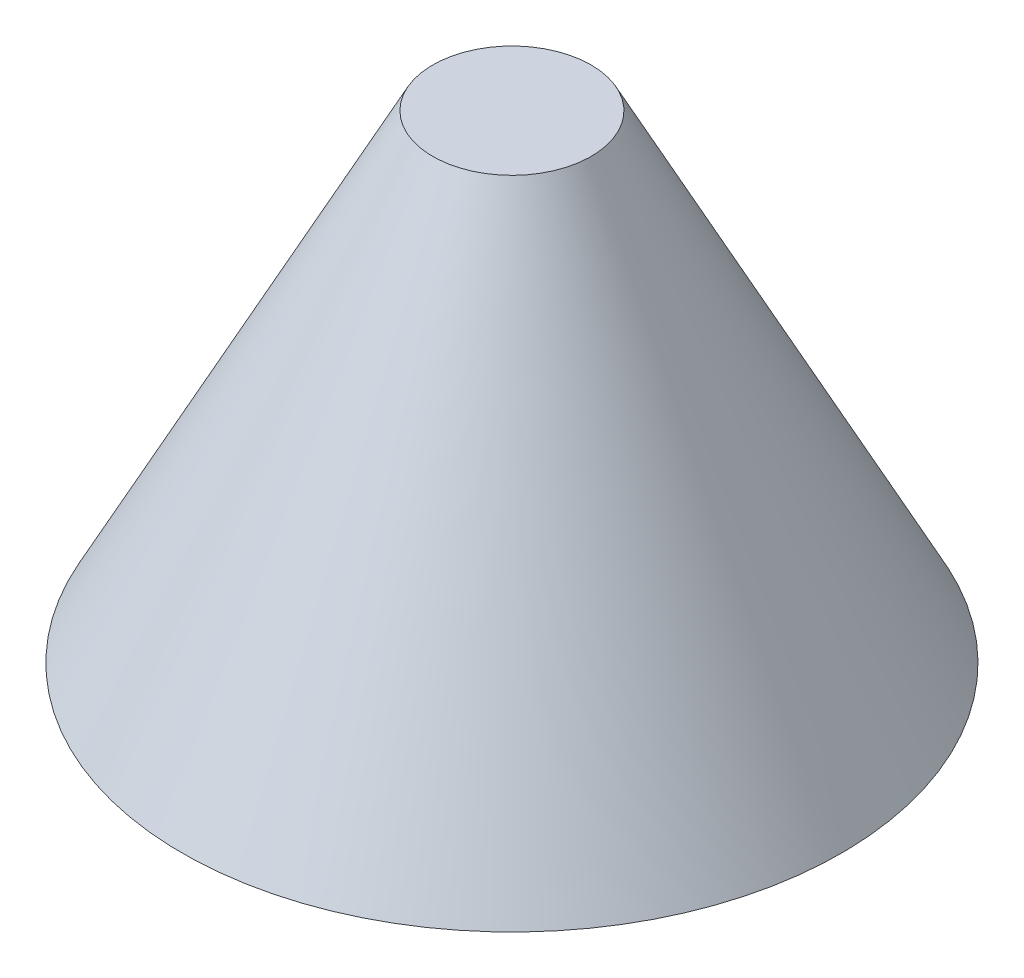
SolidWorks part; units mm, degrees
material "纯铅"
ref_plane "前视基准面" through (0, 0, 0) normal (0, 0, 1) x (1, 0, 0)
ref_plane "上视基准面" through (0, 0, 0) normal (0, 1, 0) x (1, 0, 0)
ref_plane "右视基准面" through (0, 0, 0) normal (1, 0, 0) x (0, 0, -1)
sketch "草图1" plane through (0, 0, 0) normal (0, 0, 1) x (1, 0, 0)
  line L0 (0, 0) -> (0.2, 0)
  line L1 (0, 0) -> (0, 0.2902)
  line L2 (0.2, 0) -> (0.0481, 0.2902)
  line L3 (0.0481, 0.2902) -> (0, 0.2902)
  dimension "D1" = 0.2
revolve "旋转1" add sketch "草图1" angle 360 about L1
